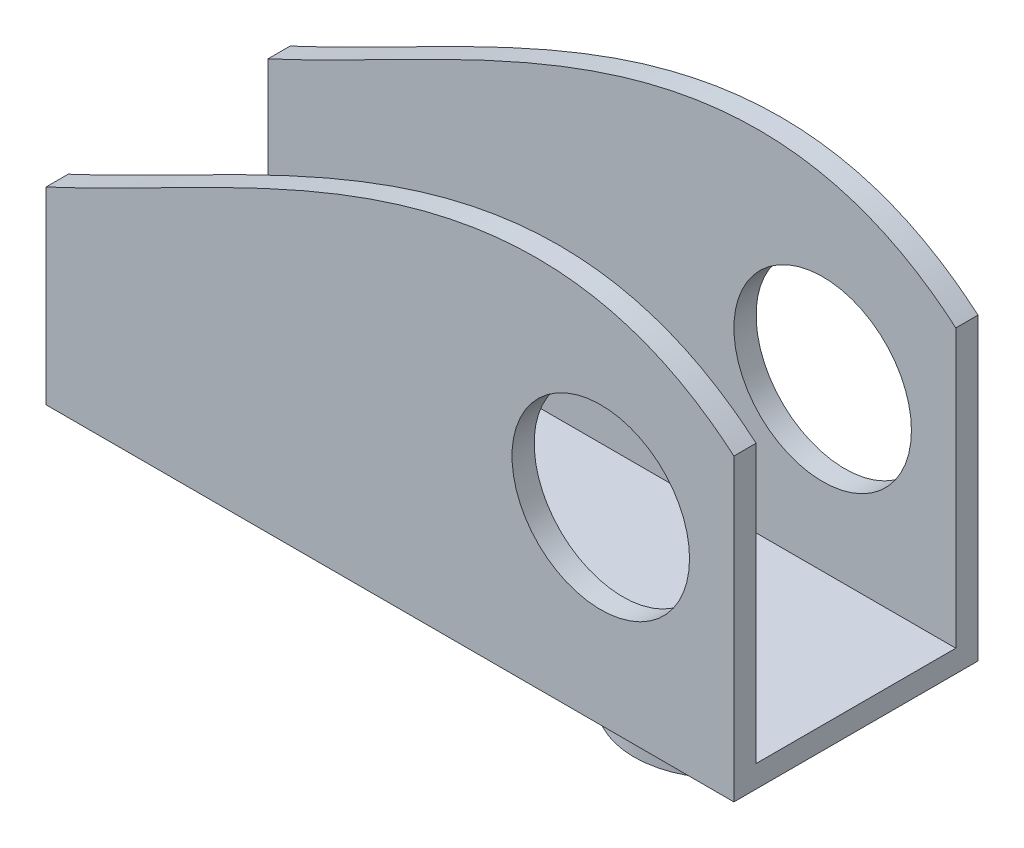
SolidWorks part; units mm, degrees
ref_plane "Front Plane" through (0, 0, 0) normal (0, 0, 1) x (1, 0, 0)
ref_plane "Top Plane" through (0, 0, 0) normal (0, 1, 0) x (1, 0, 0)
ref_plane "Right Plane" through (0, 0, 0) normal (1, 0, 0) x (0, 0, -1)
sketch "Sketch1" plane through (0, 0, 0) normal (0, 0, 1) x (1, 0, 0)
  line L0 (60, 85) -> (60, 135)
  line L1 (60, 0) -> (-250, 0)
  line L2 (60, 0) -> (60, 85)
  line L3 (60, 85) -> (-250, 85) construction
  line L4 (-250, 0) -> (-250, 85)
  line L5 (0, 85) -> (0, 165)
  spline S0 degree 3 poles (-250, 85) (-153.8013, 129.3102) (-33.7522, 215.0421) (60, 135) knots 0 0 0 0 1 1 1 1
  dimension "D1" = 250
  dimension "D2" = 60
  dimension "D3" = 85
  dimension "D4" = 50
  dimension "D5" = 80
extrude "Boss-Extrude1" add sketch "Sketch1" against normal blind 10 contours L2 L3 L4 L1 | L3 L5 S0 | L3 L0 S0 L5
sketch "Sketch2" plane through (0, 0, 0) normal (0, 1, 0) x (1, 0, 0)
  line L1 (60, 10) -> (-250, 10)
  line L2 (60, 10) -> (60, 110)
  line L3 (60, 110) -> (-250, 110)
  line L4 (-250, 10) -> (-250, 110)
  dimension "D1" = 100
extrude "Boss-Extrude2" add sketch "Sketch2" along normal blind 10
ref_plane "Plane1" through (0, 0, -55) normal (0, 0, -1) x (-1, 0, 0)
sketch "Sketch3" plane through (0, 0, 0) normal (0, 0, 1) x (1, 0, 0)
  line L1 (-250, 0) -> (-250, 85) construction
  circle A0 centre (0, 85) radius 40
  dimension "D3" = 80
  dimension "D1" = 250
  dimension "D2" = 85
extrude "Cut-Extrude1" cut sketch "Sketch3" against normal blind 10
mirror "Mirror1" about plane through (0, 0, -55) normal (0, 0, -1) of "Cut-Extrude1", "Boss-Extrude1"
sketch "Sketch4" plane through (0, 0, 0) normal (0, -1, 0) x (1, 0, 0)
  line L0 (-96.2616, -55) -> (96.2616, -55) construction
  circle A0 centre (0, -55) radius 40
  dimension "D1" = 80
extrude "Boss-Extrude3" add sketch "Sketch4" along normal blind 20
